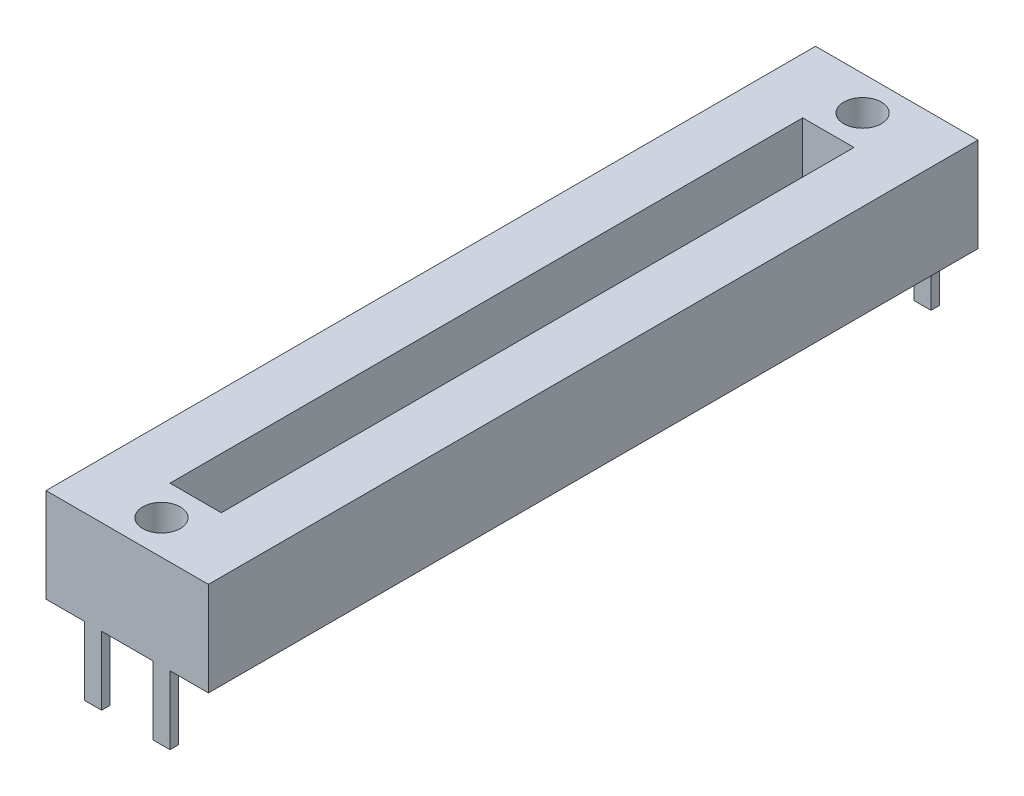
SolidWorks part; units mm, degrees
ref_plane "前视基准面" through (0, 0, 0) normal (0, 0, 1) x (1, 0, 0)
ref_plane "上视基准面" through (0, 0, 0) normal (0, 1, 0) x (1, 0, 0)
ref_plane "右视基准面" through (0, 0, 0) normal (1, 0, 0) x (0, 0, -1)
sketch "草图1" plane through (0, 0, 0) normal (0, 1, 0) x (1, 0, 0)
  line L1 (-4.75, -22.5) -> (4.75, -22.5)
  line L2 (-4.75, -22.5) -> (-4.75, 22.5)
  line L3 (-4.75, 22.5) -> (4.75, 22.5)
  line L4 (4.75, -22.5) -> (4.75, 22.5)
  line L5 (-4.75, -22.5) -> (4.75, 22.5) construction
  line L6 (-4.75, 22.5) -> (4.75, -22.5) construction
  point P0 (0, 0)
  dimension "D1" = 9.5
  dimension "D2" = 45
extrude "凸台-拉伸1" add sketch "草图1" along normal blind 5.5
sketch "草图2" plane through (0, 5.5, 0) normal (0, 1, 0) x (1, 0, 0)
  line L1 (-1.5, -18.5) -> (1.5, -18.5)
  line L2 (-1.5, -18.5) -> (-1.5, 18.5)
  line L3 (-1.5, 18.5) -> (1.5, 18.5)
  line L4 (1.5, -18.5) -> (1.5, 18.5)
  line L5 (-1.5, -18.5) -> (1.5, 18.5) construction
  line L6 (-1.5, 18.5) -> (1.5, -18.5) construction
  point P0 (0, 0)
  dimension "D1" = 37
  dimension "D2" = 3
extrude "切除-拉伸1" cut sketch "草图2" against normal blind 3
sketch "草图3" plane through (0, 5.5, 0) normal (0, 1, 0) x (1, 0, 0)
  line L0 (0, 0) -> (15.8052, 0) construction
  line L1 (0, -20.5) -> (0, 0) construction
  circle A0 centre (0, -20.5) radius 1.1
  circle A1 centre (0, 20.5) radius 1.1
  dimension "D1" = 2.2
  dimension "D2" = 41
extrude "切除-拉伸2" cut sketch "草图3" against normal blind 3
sketch "草图4" plane through (0, 0, 0) normal (0, -1, 0) x (1, 0, 0)
  line L5 (-4.75, 22.5) -> (4.75, 22.5) construction
  line L6 (2.5, 22.5) -> (1.5, 22.5)
  line L7 (2.5, 22.5) -> (2.5, 22)
  line L8 (2.5, 22) -> (1.5, 22)
  line L9 (1.5, 22.5) -> (1.5, 22)
  line L10 (0, 0) -> (0, 23.7591) construction
  line L11 (0, 0) -> (8.1592, 0) construction
  line L12 (-2.5, 22.5) -> (-2.5, 22)
  line L13 (-2.5, 22.5) -> (-1.5, 22.5)
  line L14 (-1.5, 22.5) -> (-1.5, 22)
  line L15 (-2.5, 22) -> (-1.5, 22)
  line L16 (2.5, -22.5) -> (2.5, -22)
  line L17 (2.5, -22.5) -> (1.5, -22.5)
  line L18 (1.5, -22.5) -> (1.5, -22)
  line L19 (2.5, -22) -> (1.5, -22)
  point P18 (1.5, 22.25)
  dimension "D1" = 1
  dimension "D2" = 3
  dimension "D3" = 0.5
extrude "凸台-拉伸2" add sketch "草图4" along normal blind 4
